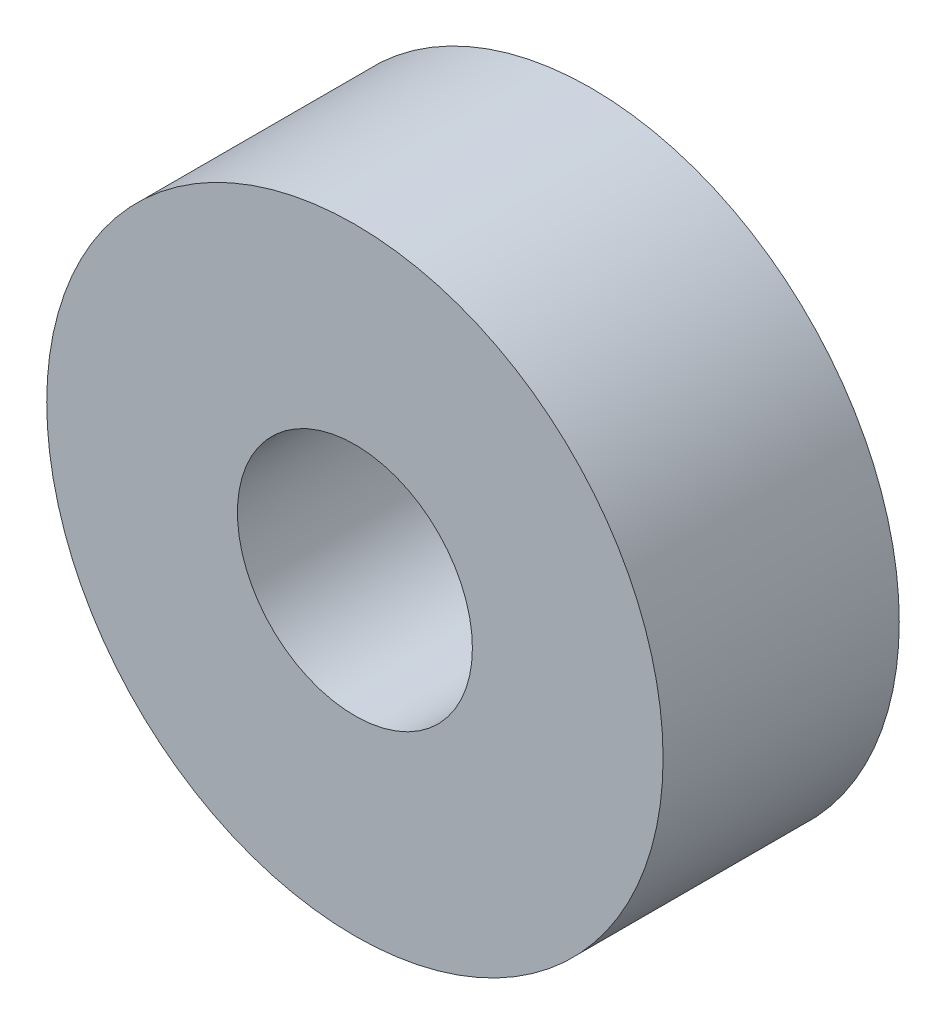
SolidWorks part; units mm, degrees
material "Plain Carbon Steel"
ref_plane "Front" through (0, 0, 0) normal (0, 0, 1) x (1, 0, 0)
ref_plane "Top" through (0, 0, 0) normal (0, 1, 0) x (1, 0, 0)
ref_plane "Right" through (0, 0, 0) normal (1, 0, 0) x (0, 0, -1)
sketch "Sketch1" plane through (0, 0, 0) normal (0, 0, 1) x (1, 0, 0)
  circle A0 centre (0, 0) radius 12.9921
  circle A1 centre (0, 0) radius 4.953
  dimension "D1" = 9.906
  dimension "D2" = 25.9842
extrude "Extrude1" add sketch "Sketch1" along normal blind 9.9568
